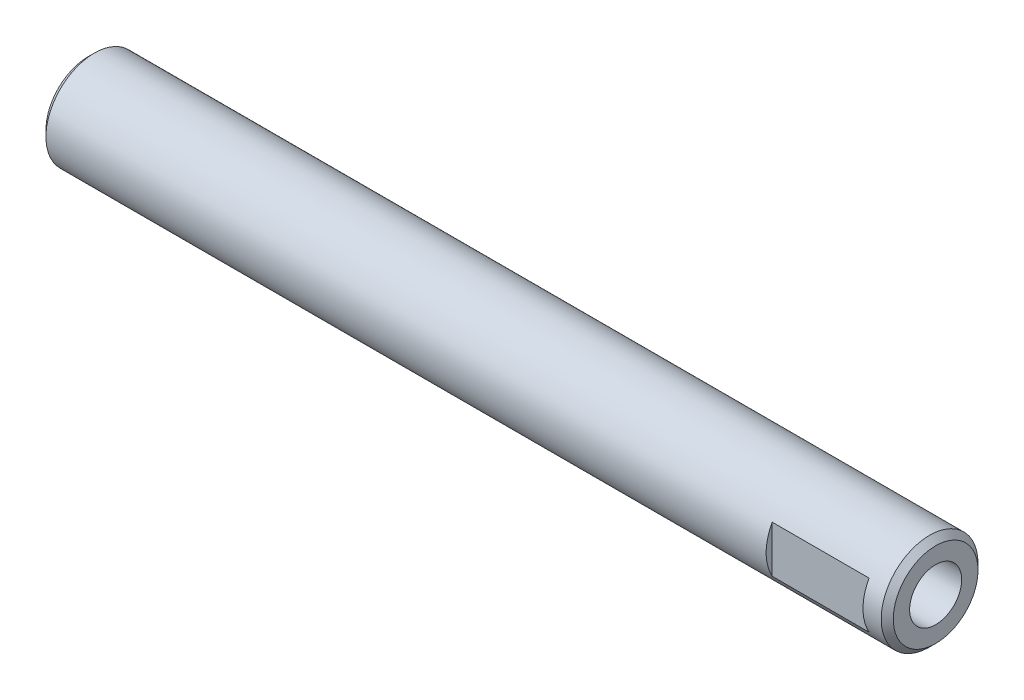
SolidWorks part; units mm, degrees
ref_plane "前视基准面" through (0, 0, 0) normal (0, 0, 1) x (1, 0, 0)
ref_plane "上视基准面" through (0, 0, 0) normal (0, 1, 0) x (1, 0, 0)
ref_plane "右视基准面" through (0, 0, 0) normal (1, 0, 0) x (0, 0, -1)
sketch "草图1" plane through (0, 0, 0) normal (0, 0, 1) x (1, 0, 0)
  line L0 (0, 0) -> (50000, 0) construction
  line L1 (0, 0) -> (0, 50000) construction
  line L2 (-25, 2.15) -> (-23.7081, 0)
  line L3 (-35, 4) -> (35, 4)
  line L4 (-35, 4) -> (-35, 0)
  line L5 (-35, 0) -> (35, 0)
  line L6 (35, 4) -> (35, 0)
  line L8 (-35, 0) -> (-35, 2.15)
  line L9 (-35, 2.15) -> (-25, 2.15)
  line L12 (35, 0) -> (35, 2.15)
  line L13 (35, 2.15) -> (25, 2.15)
  line L15 (25, 2.15) -> (23.7081, 0)
  dimension "D1" = 70
  dimension "D2" = 8
  dimension "D3" = 59
  dimension "D4" = 59
  dimension "D5" = 10
  dimension "D6" = 4.3
  dimension "D7" = 4.3
  dimension "D8" = 10
revolve "旋转1" add sketch "草图1" angle 360 about L0
cosmetic thread "装饰螺纹线1" parameters "D2"=5
cosmetic thread "装饰螺纹线2" parameters "D2"=5
ref_plane "基准面2" through (0, 4, 0) normal (0, 1, 0) x (1, 0, 0)
chamfer "倒角1" distance 0.5 angle 45 2 edges at (35, 0, 4) (-35, 0, 4)
ref_plane "基准面1" through (25, 0, 0) normal (-1, 0, 0) x (0, 0, 1)
sketch "草图2" plane through (25, 0, 0) normal (-1, 0, 0) x (0, 0, 1)
  line L1 (-3.5, -4) -> (3.5, -4)
  line L2 (-3.5, -4) -> (-3.5, 4)
  line L3 (-3.5, 4) -> (3.5, 4)
  line L4 (3.5, -4) -> (3.5, 4)
  line L5 (-3.5, -4) -> (3.5, 4) construction
  line L6 (-3.5, 4) -> (3.5, -4) construction
  circle A0 centre (0, 0) radius 4 construction
  point P0 (0, 0)
  dimension "D1" = 7
extrude "切除-拉伸1" cut sketch "草图2" against normal blind 8 flip side to cut
sketch "草图3" plane through (0, 0, 0) normal (0, 0, 1) x (1, 0, 0)
  line L0 (0, 0) -> (50000, 0) construction
  line L1 (-35, 3.5) -> (-35, -3.5) construction
  circle A0 centre (-15, 0) radius 1.5
  dimension "D1" = 3
  dimension "D2" = 20
extrude "切除-拉伸2" [suppressed] cut sketch "草图3" against normal up to next and the other way up to next
sketch "草图4" [suppressed] plane through (0, 6, 0) normal (0, 1, 0) x (1, 0, 0)
  line L0 (25, -5.5) -> (25, 5.5) construction
  line L1 (9, 6.5) -> (15, 6.5)
  line L2 (9, 6.5) -> (9, -6.5)
  line L3 (9, -6.5) -> (15, -6.5)
  line L4 (15, 6.5) -> (15, -6.5)
  line L5 (9, 6.5) -> (15, -6.5) construction
  line L6 (9, -6.5) -> (15, 6.5) construction
  point P0 (12, 0)
  dimension "D1" = 9
  dimension "D2" = 6
  dimension "D3" = 10
  dimension "D4" = 10
extrude "切除-拉伸3" [suppressed] cut sketch "草图4" against normal blind 1
sketch "草图5" [suppressed] plane through (0, 6, 0) normal (0, 1, 0) x (1, 0, 0)
  line L0 (25, -5.5) -> (25, 5.5) construction
  line L1 (-21, 6.5) -> (-15, 6.5)
  line L2 (-21, 6.5) -> (-21, -6.5)
  line L3 (-21, -6.5) -> (-15, -6.5)
  line L4 (-15, 6.5) -> (-15, -6.5)
  line L5 (-21, 6.5) -> (-15, -6.5) construction
  line L6 (-21, -6.5) -> (-15, 6.5) construction
  line L7 (9, 6.5) -> (15, 6.5)
  line L8 (9, 6.5) -> (9, -6.5)
  line L9 (9, -6.5) -> (15, -6.5)
  line L10 (15, 6.5) -> (15, -6.5)
  line L11 (9, 6.5) -> (15, -6.5) construction
  line L12 (9, -6.5) -> (15, 6.5) construction
  line L13 (-25, 5.5) -> (-25, -5.5) construction
  point P0 (-18, 0)
  point P5 (12, 0)
  dimension "D1" = 9
  dimension "D2" = 9
  dimension "D3" = 10
  dimension "D4" = 6
  dimension "D5" = 6
  dimension "D6" = 4
extrude "切除-拉伸4" [suppressed] cut sketch "草图5" against normal blind 1
